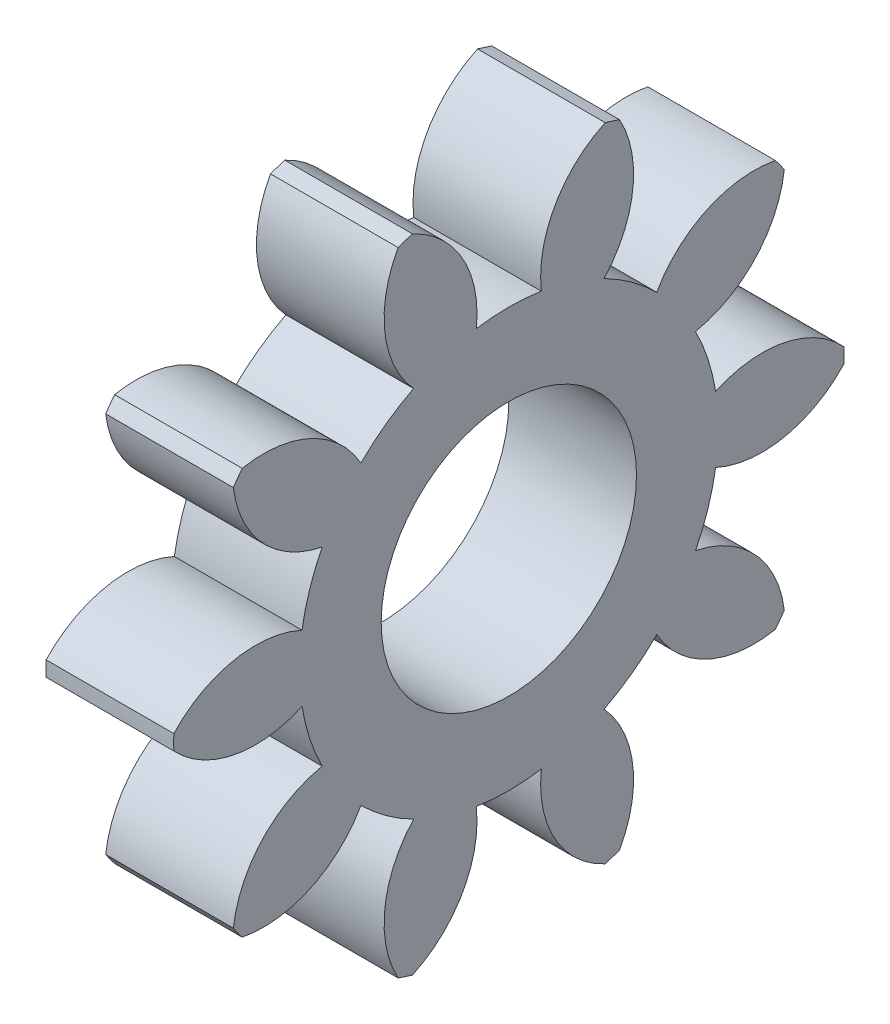
SolidWorks part; units mm, degrees
ref_plane "Plane1" through (0, 0, 0) normal (0, 0, 1) x (1, 0, 0)
ref_plane "Plane2" through (0, 0, 0) normal (0, 1, 0) x (1, 0, 0)
ref_plane "Plane3" through (0, 0, 0) normal (1, 0, 0) x (0, 0, -1)
other "Configuration Table"
sketch "HoldingSke" plane through (0, 0, 0) normal (0, 1, 0) x (1, 0, 0)
  line L0 (0, 0) -> (0.5627, -0.0992)
  line L1 (-15, 0) -> (100, 0) construction
  line L2 (0, 0) -> (-2.1039, 2.3779)
  line L3 (0, 0) -> (-11.863, 4.5341)
  line L4 (0, 0) -> (8.5048, 1.4996)
  line L5 (0, 0) -> (-46.8476, -17.4728)
  line L6 (0, 0) -> (-3.3159, -2.2372)
  line L7 (-2.1039, 2.3779) -> (8.6586, 51.2059)
  line L8 (-76.2, 54.61) -> (-76.1, 54.61)
  line L9 (-71.009, 38.7566) -> (-53.1078, 45.2721)
  line L10 (-76.2, 71.12) -> (104.1128, 71.12)
  line L11 (0, 0) -> (-4, 0)
  line L12 (-76.2, 101.6) -> (-76.147, 101.6)
  line L13 (24.9733, 27.94) -> (52.9518, 28.4284)
  line L14 (24.9733, 27.94) -> (24.9743, 27.94)
  line L15 (24.9733, 27.94) -> (100.4006, 29.5858)
  line L16 (-63.627, -1.75) -> (-12.827, -1.75)
  circle A0 centre (0, 0) radius 0.5
  circle A1 centre (0, 0) radius 6.5615
  circle A2 centre (0, 0) radius 37.5
  circle A3 centre (0, 0) radius 0.5
  dimension "MHD" = 13.123
  dimension "Hub_dia" = 75
  dimension "Bore" = 1
  dimension "MBD" = 1
  dimension "Num_teeth" = 10
  dimension "Pitch" = 0.5714
  dimension "Overall_len" = 50
  dimension "Show_teeth" = 10
  dimension "Thickness" = 4
  dimension "OAL" = 50.0001
  dimension "T_dim" = 0.1
  dimension "Ap" = 20
  dimension "H" = 19.05
  dimension "Pitch_radius" = 180.3128
  dimension "Width" = 4
  dimension "Backlash" = 0.053
  dimension "Addendum_fac" = 1
  dimension "Dedendum_fac" = 1.25
  dimension "Clearance_fac" = 0.25
  dimension "Dedendum_add" = 0.001
  dimension "Module" = 1.75
sketch "BasProSke" plane through (0, 0, 0) normal (0, 1, 0) x (1, 0, 0)
  line L0 (-10, 0) -> (60, 0) construction
  line L1 (0, 0) -> (0, 10.5)
  line L2 (0, 0) -> (4, 0)
  line L3 (4, 0) -> (4, 10.5)
  line L4 (4, 10.5) -> (0, 10.5)
  dimension "Thickness" = 4
  dimension "Diameter" = 21
revolve "Base-Revolve" add sketch "BasProSke" angle 360 about L0
sketch "TooCutSke" plane through (0, 0, 0) normal (1, 0, 0) x (0, 0, -1)
  line L1 (0, 0) -> (0, 107) construction
  line L2 (0, 0) -> (-1.4614, 8.6271) construction
  line L3 (0, 0) -> (-5.35, 16.4656) construction
  line L4 (-1.4614, 8.6271) -> (-2.675, 8.2328) construction
  arc A0 (1.0196, 6.4818) -> (-1.0196, 6.4818) centre (0, 0) ccw
  arc A1 (3.0536, 10.0727) -> (-3.0536, 10.0727) centre (0, 0) ccw
  circle A2 centre (0, 0) radius 8.75 construction
  circle A3 centre (0, 0) radius 8.2223 construction
  arc A4 (-1.0196, 6.4818) -> (-3.0536, 10.0727) centre (-4.4964, 6.8839) ccw
  arc A5 (3.0536, 10.0727) -> (1.0196, 6.4818) centre (4.4964, 6.8839) ccw
  dimension "Root_dia" = 13.123
  dimension "Overcut_dia" = 21.0508
  dimension "Pitch_dia" = 17.5
  dimension "Base_dia" = 16.4446
  dimension "Flank_rad" = 3.5
  dimension "Half_ang" = 18
  dimension "Half_CT" = 1.2761
extrude "ToothCut" cut sketch "TooCutSke" along normal through all
fillet "Breaks" [suppressed] radius 0.035
fillet "RootFillets" [suppressed] radius 0.4385
pattern_circular "TeethCuts" count 10 every 36 about axis through (-10, 0, 0) along (1, 0, 0) of "ToothCut", "RootFillets", "Breaks"
sketch "HubNeaOneSke" plane through (0, 0, 0) normal (-1, 0, 0) x (0, 0, 1)
  circle A0 centre (0, 0) radius 6.5615
  dimension "Diameter" = 13.123
extrude "HubNearOne" [suppressed] add sketch "HubNeaOneSke" along normal blind 46.0001
sketch "HubNeaBotSke" plane through (0, 0, 0) normal (-1, 0, 0) x (0, 0, 1)
  circle A0 centre (0, 0) radius 6.5615
  dimension "Diameter" = 13.123
extrude "HubNearBoth" [suppressed] add sketch "HubNeaBotSke" along normal blind 23
ref_plane "FarPln" through (4, 0, 0) normal (1, 0, 0) x (0, 0, -1)
sketch "HubFarSke" plane through (4, 0, 0) normal (1, 0, 0) x (0, 0, -1)
  circle A0 centre (0, 0) radius 6.5615
  dimension "Diameter" = 13.123
extrude "HubFar" [suppressed] add sketch "HubFarSke" along normal blind 23
sketch "BorSke" plane through (0, 0, 0) normal (1, 0, 0) x (0, 0, -1)
  circle A0 centre (0, 0) radius 0.5
  dimension "Diameter" = 1
extrude "Bore" cut sketch "BorSke" along normal mid plane 100.0001
sketch "KeySke" plane through (0, 0, 0) normal (1, 0, 0) x (0, 0, -1)
  line L0 (-0.05, 0) -> (-0.05, 0.6)
  line L1 (-0.05, 0.6) -> (0.05, 0.6)
  line L2 (0.05, 0.6) -> (0.05, 0)
  line L3 (0, 0) -> (0, 34) construction
  line L4 (-0.05, 0) -> (0.05, 0)
  dimension "Offset" = 0.6
  dimension "Width" = 0.1
extrude "Keyway" [suppressed] cut sketch "KeySke" along normal mid plane 100.0001
pattern_circular "Keyway2" [suppressed] count 2 every 90 about axis through (-10, 0, 0) along (1, 0, 0)
sketch "Sketch1" plane through (4, 0, 0) normal (1, 0, 0) x (0, 0, -1)
  circle A0 centre (0, 0) radius 4
  dimension "D1" = 8
extrude "Cut-Extrude1" cut sketch "Sketch1" against normal blind 10
equation "' \"Module@HoldingSke\" = 6.35"
equation "' \"Num_teeth@HoldingSke\" = 12"
equation "' \"Ap@HoldingSke\" =  20"
equation "' \"Ap@HoldingSke\" = 20"
equation "' \"Width@HoldingSke\" = 0.5 * 25.4"
equation "' \"Hub_dia@HoldingSke\"= 1 * 25.4"
equation "' \"Hub_dia@HoldingSke\" = 1 * 25.4"
equation "' \"Overall_len@HoldingSke\" = 1.0 * 25.4"
equation "' \"Bore@HoldingSke\" = 0.75 * 25.4"
equation "' \"T_dim@HoldingSke\" = 0.1 * 25.4"
equation "' \"Width@KeySke\" = 0.25 * 25.4"
equation "' \"Show_teeth@HoldingSke\" = 13"
equation "' \"Backlash@HoldingSke\" = 0.009 * 25.4"
equation "' \"Addendum_fac@HoldingSke\" = 1.0"
equation "' \"Dedendum_fac@HoldingSke\" = 1.25"
equation "' \"Dedendum_add@HoldingSke\" = 0.00005 * 25.4"
equation "' \"Clearance_fac@HoldingSke\" = 0.25"
equation "\"Pitch@HoldingSke\" = 1 / \"Module@HoldingSke\""
equation "\"Overcut_dia@TooCutSke\" = (\"Num_teeth@HoldingSke\" + 2 * \"Addendum_fac@HoldingSke\") / \"Pitch@HoldingSke\" + 0.002 * 25.4"
equation "\"Pitch_dia@TooCutSke\" = \"Num_teeth@HoldingSke\" / \"Pitch@HoldingSke\""
equation "\"Base_dia@TooCutSke\" = \"Num_teeth@HoldingSke\" / \"Pitch@HoldingSke\" * cos((\"Ap@HoldingSke\"  * 3.14159265 / 180))"
equation "\"Root_dia@TooCutSke\" = (\"Num_teeth@HoldingSke\" + 2) / \"Pitch@HoldingSke\" - 2 * (\"Addendum_fac@HoldingSke\" + \"Dedendum_fac@HoldingSke\") / \"Pitch@HoldingSke\" - \"Dedendum_add@HoldingSke\" * 2"
equation "\"Half_ang@TooCutSke\" = 180 / \"Num_teeth@HoldingSke\""
equation "\"Half_CT@TooCutSke\" = \"Num_teeth@HoldingSke\" / \"Pitch@HoldingSke\" * sin((3.14159265 / 2 / \"Num_teeth@HoldingSke\")) / 2 - 7 * \"Backlash@HoldingSke\" / 4"
equation "\"Flank_rad@TooCutSke\" = \"Num_teeth@HoldingSke\" / \"Pitch@HoldingSke\" / 5"
equation "\"Radius@RootFillets\" = \"Clearance_fac@HoldingSke\" / \"Pitch@HoldingSke\" + \"Dedendum_add@HoldingSke\""
equation "\"Break_rad@Breaks\" = 0.02 / \"Pitch@HoldingSke\""
equation "\"Thickness@HoldingSke\" = \"Width@HoldingSke\""
equation "\"OAL@HoldingSke\" = \"Thickness@HoldingSke\""
equation "\"MHD@HoldingSke\" = (\"Num_teeth@HoldingSke\" + 2) / \"Pitch@HoldingSke\" - 2 * (\"Addendum_fac@HoldingSke\" + \"Dedendum_fac@HoldingSke\")  / \"Pitch@HoldingSke\" - \"Dedendum_add@HoldingSke\" * 2"
equation "\"MBD@HoldingSke\" = (\"Num_teeth@HoldingSke\" + 2) / \"Pitch@HoldingSke\" - 2 * (\"Addendum_fac@HoldingSke\" + \"Dedendum_fac@HoldingSke\")  / \"Pitch@HoldingSke\" - \"Dedendum_add@HoldingSke\" * 2 - 0.002 * 25.4"
equation "\"MHD@HoldingSke\" = ((sgn( \"MHD@HoldingSke\" - \"Hub_dia@HoldingSke\" )-1)*( \"MHD@HoldingSke\" - \"Hub_dia@HoldingSke\" ))/-2+ \"Hub_dia@HoldingSke\""
equation "\"MBD@HoldingSke\" = ((sgn( \"MBD@HoldingSke\" - \"Bore@HoldingSke\" )-1)*( \"MBD@HoldingSke\" - \"Bore@HoldingSke\" ))/-2+ \"Bore@HoldingSke\""
equation "\"OAL@HoldingSke\" = ((sgn( \"OAL@HoldingSke\" - \"Overall_len@HoldingSke\" )+1)*( \"OAL@HoldingSke\" - \"Overall_len@HoldingSke\" ))/2 + \"Overall_len@HoldingSke\" + 0.000002 * 25.4"
equation "\"Num_teeth@TeethCuts\" = int( \"Show_teeth@HoldingSke\" ) + 1"
equation "\"Num_teeth@TeethCuts\" = ((sgn( \"Num_teeth@TeethCuts\" - \"Num_teeth@HoldingSke\" )-1)*( \"Num_teeth@TeethCuts\" - \"Num_teeth@HoldingSke\" ))/-2+ \"Num_teeth@HoldingSke\""
equation "\"Num_teeth@TeethCuts\" = ((sgn( \"Num_teeth@TeethCuts\" - 2.0)+1)*( \"Num_teeth@TeethCuts\" - 2.0))/2 +2.0"
equation "\"Angle@TeethCuts\" = 360.0 / \"Num_teeth@HoldingSke\""
equation "\"Diameter@BasProSke\" = (\"Num_teeth@HoldingSke\" + 2 * \"Addendum_fac@HoldingSke\") / \"Pitch@HoldingSke\""
equation "\"Thickness@BasProSke\"  = \"Thickness@HoldingSke\""
equation "' \"Fillet_rad@BasProSke\" =  \"Thickness@HoldingSke\" * 0.05"
equation "' \"Fillet_rad@BasProSke\" = \"Thickness@HoldingSke\" * 0.05"
equation "\"MHD@HoldingSke\" = ((sgn( \"MHD@HoldingSke\" - \"Root_dia@TooCutSke\" )-1)*( \"MHD@HoldingSke\" - \"Root_dia@TooCutSke\" ))/-2+ \"Root_dia@TooCutSke\""
equation "\"Diameter@HubNeaOneSke\" = \"MHD@HoldingSke\""
equation "\"Length@HubNearOne\" = \"OAL@HoldingSke\" - \"Thickness@BasProSke\""
equation "\"Diameter@HubNeaBotSke\" = \"MHD@HoldingSke\""
equation "\"Length@HubNearBoth\" = ( \"OAL@HoldingSke\" - \"Thickness@BasProSke\" ) / 2.0"
equation "\"Thickness@FarPln\" = \"Thickness@BasProSke\""
equation "\"Diameter@HubFarSke\" = \"MHD@HoldingSke\""
equation "\"Length@HubFar\" = ( \"OAL@HoldingSke\" - \"Thickness@BasProSke\" ) / 2.0"
equation "\"Diameter@BorSke\" = \"MBD@HoldingSke\""
equation "\"D1@Bore\" = \"OAL@HoldingSke\" * 2.0"
equation "\"D1@Keyway\" = \"OAL@HoldingSke\" * 2.0"
equation "\"Offset@KeySke\" = \"T_dim@HoldingSke\" + \"MBD@HoldingSke\" / 2.0"
